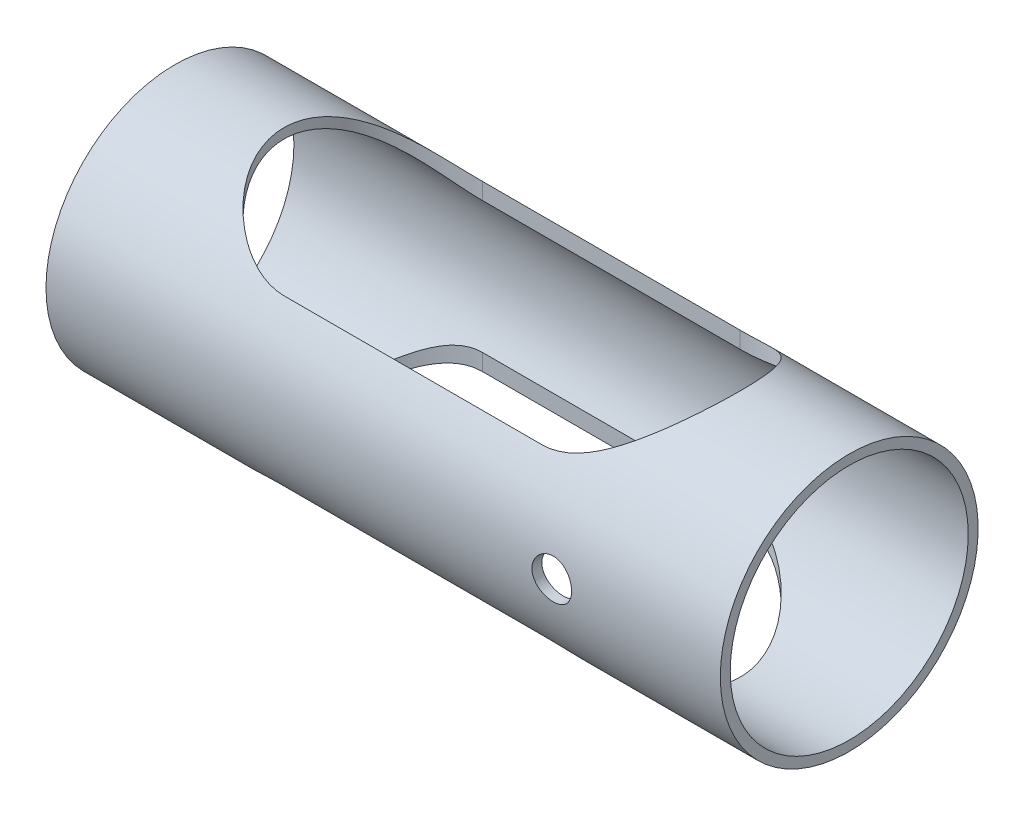
SolidWorks part; units mm, degrees
ref_plane "Front Plane" through (0, 0, 0) normal (0, 0, 1) x (1, 0, 0)
ref_plane "Top Plane" through (0, 0, 0) normal (0, 1, 0) x (1, 0, 0)
ref_plane "Right Plane" through (0, 0, 0) normal (1, 0, 0) x (0, 0, -1)
sketch "Sketch1" plane through (0, 0, 0) normal (0, 0, 1) x (1, 0, 0)
  line L0 (-43.2695, 0) -> (43.2695, 0) construction
  line L1 (-34, 12) -> (34, 12)
  line L2 (34, 12) -> (34, 13)
  line L3 (34, 13) -> (-34, 13)
  line L4 (-34, 13) -> (-34, 12)
  point P4 (0, 0)
  point P7 (0, 12)
  dimension "D1" = 68
  dimension "D2" = 12
  dimension "D3" = 13
revolve "Revolve1" add sketch "Sketch1" angle 360 about L0
sketch "Sketch2" plane through (0, 0, 0) normal (0, 1, 0) x (1, 0, 0)
  line L0 (-13, 0) -> (13, 0) construction
  line L2 (-13, 10) -> (13, 10)
  line L3 (-13, -10) -> (13, -10)
  arc A0 (-13, 10) -> (-13, -10) centre (-13, 0) ccw
  arc A1 (13, -10) -> (13, 10) centre (13, 0) ccw
  point P5 (0, 0)
  dimension "D1" = 20
  dimension "D2" = 26
extrude "Cut-Extrude1" cut sketch "Sketch2" against normal through all both and the other way through all
sketch "Sketch3" plane through (0, 0, 0) normal (0, 0, 1) x (1, 0, 0)
  line L1 (34, -13) -> (34, 13) construction
  circle A1 centre (17, 0) radius 2
  dimension "D1" = 4
  dimension "D2" = 17
extrude "Cut-Extrude2" cut sketch "Sketch3" along normal through all
